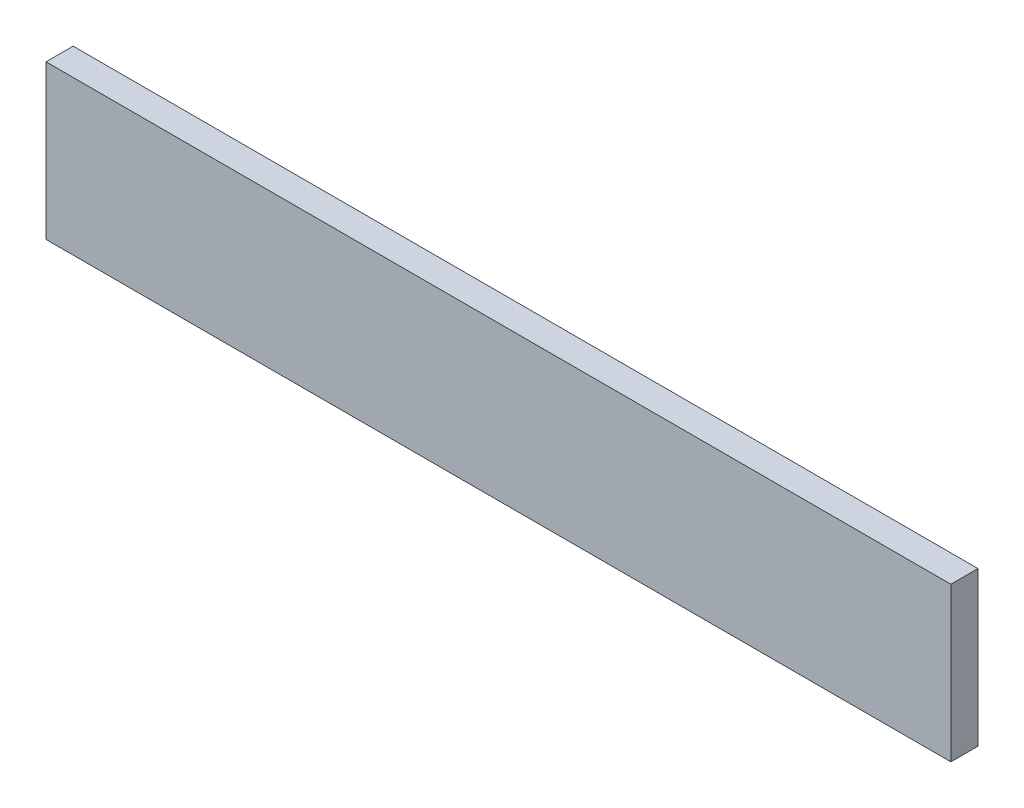
SolidWorks part; units mm, degrees
ref_plane "Front Plane" through (0, 0, 0) normal (0, 0, 1) x (1, 0, 0)
ref_plane "Top Plane" through (0, 0, 0) normal (0, 1, 0) x (1, 0, 0)
ref_plane "Right Plane" through (0, 0, 0) normal (1, 0, 0) x (0, 0, -1)
sketch "Sketch1" plane through (0, 0, 0) normal (0, 0, 1) x (1, 0, 0)
  line L1 (-50, 8.5) -> (50, 8.5)
  line L2 (-50, 8.5) -> (-50, -8.5)
  line L3 (-50, -8.5) -> (50, -8.5)
  line L4 (50, 8.5) -> (50, -8.5)
  line L5 (-50, 8.5) -> (50, -8.5) construction
  line L6 (-50, -8.5) -> (50, 8.5) construction
  point P0 (0, 0)
  dimension "D1" = 100
  dimension "D2" = 17
extrude "Boss-Extrude1" add sketch "Sketch1" along normal blind 3
